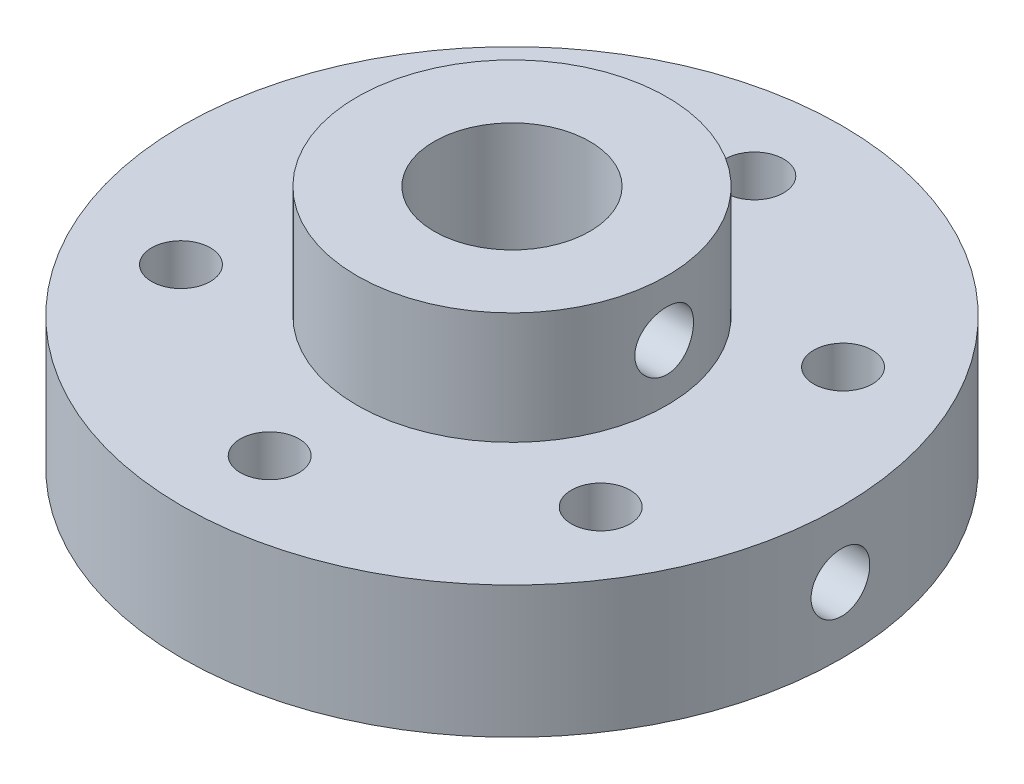
SolidWorks part; units mm, degrees
ref_plane "Front Plane" through (0, 0, 0) normal (0, 0, 1) x (1, 0, 0)
ref_plane "Top Plane" through (0, 0, 0) normal (0, 1, 0) x (1, 0, 0)
ref_plane "Right Plane" through (0, 0, 0) normal (1, 0, 0) x (0, 0, -1)
sketch "Sketch8" plane through (0, 0, 0) normal (0, 1, 0) x (1, 0, 0)
  circle A0 centre (0, 0) radius 12.7
  dimension "D1" = 25.4
extrude "Boss-Extrude6" add sketch "Sketch8" along normal blind 5.08
sketch "Sketch9" plane through (0, 5.08, 0) normal (0, 1, 0) x (1, 0, 0)
  circle A0 centre (0, 0) radius 5.969
  dimension "D1" = 11.938
extrude "Boss-Extrude7" add sketch "Sketch9" along normal blind 4.318
hole_wizard "#4-40 Tapped Hole1" positions "Sketch11" profile "Sketch10" tap size "#4-40" standard "ANSI Inch" end condition through all
sketch "Sketch11" plane through (0, 5.08, 0) normal (0, 1, 0) x (1, 0, 0)
  line L2 (0, 5.969) -> (0, 12.7) construction
  circle A1 centre (0, 0) radius 5.969 construction
  circle A2 centre (0, 0) radius 5.969 construction
  circle A3 centre (0, 0) radius 12.7 construction
  point P0 (0, 9.3345)
sketch "Sketch10" plane through (0, 5.08, -9.3345) normal (1, 0, 0) x (0, 0, 1)
  line L0 (0, 0) -> (0, 5.08)
  line L1 (0, 5.08) -> (1.1303, 5.08)
  line L2 (1.1303, 5.08) -> (1.1303, 0)
  line L5 (1.1303, 0) -> (0, 0)
  line L11 (0, -6.35) -> (0, 107.95) construction
  dimension "Thread Major Dia." = 2.2606
  dimension "Thru Tap Drill Depth" = 5.08
pattern_circular "CirPattern1" count 6 over 360 about axis through (0, 0, 0) along (0, 1, 0) of "#4-40 Tapped Hole1"
sketch "Sketch12" plane through (0, 9.398, 0) normal (0, 1, 0) x (1, 0, 0)
  circle A0 centre (0, 0) radius 3
  dimension "D1" = 6
extrude "Cut-Extrude2" cut sketch "Sketch12" against normal through all
hole_wizard "#4-40 Tapped Hole2" positions "Sketch14" profile "Sketch13" tap size "#4-40" standard "ANSI Inch"
sketch "Sketch14" plane through (0, 0, 0) normal (1, 0, 0) x (0, 0, -1)
  line L0 (0, 9.398) -> (0, 5.08) construction
  line L1 (5.969, 9.398) -> (-5.969, 9.398) construction
  line L2 (12.7, 5.08) -> (-12.7, 5.08) construction
  line L3 (0, 5.08) -> (0, 0) construction
  point P3 (0, 7.239)
  point P5 (0, 2.54)
sketch "Sketch13" plane through (0, 7.239, 0) normal (0, 1, 0) x (0, 0, 1)
  line L0 (0, 0) -> (0, 12.7)
  line L1 (0, 12.7) -> (1.1303, 12.7)
  line L2 (1.1303, 12.7) -> (1.1303, 0)
  line L5 (1.1303, 0) -> (0, 0)
  line L11 (0, -6.35) -> (0, 107.95) construction
  dimension "Thread Major Dia." = 2.2606
  dimension "Thru Tap Drill Depth" = 12.7
sketch "Sketch15" plane through (0, 5.08, 0) normal (0, 1, 0) x (1, 0, 0)
  line L0 (-9.2142, -4.6672) -> (-6.9536, -4.6672) construction
  line L1 (6.9536, 4.6672) -> (9.2142, 4.6672) construction
  line L2 (-8.0839, -4.6672) -> (8.0839, 4.6672) construction
  circle A0 centre (-8.0839, -4.6672) radius 1.1303 construction
  circle A1 centre (8.0839, 4.6672) radius 1.1303 construction
  dimension "D1" = 18.669
  dimension "D2" = 2.2606
